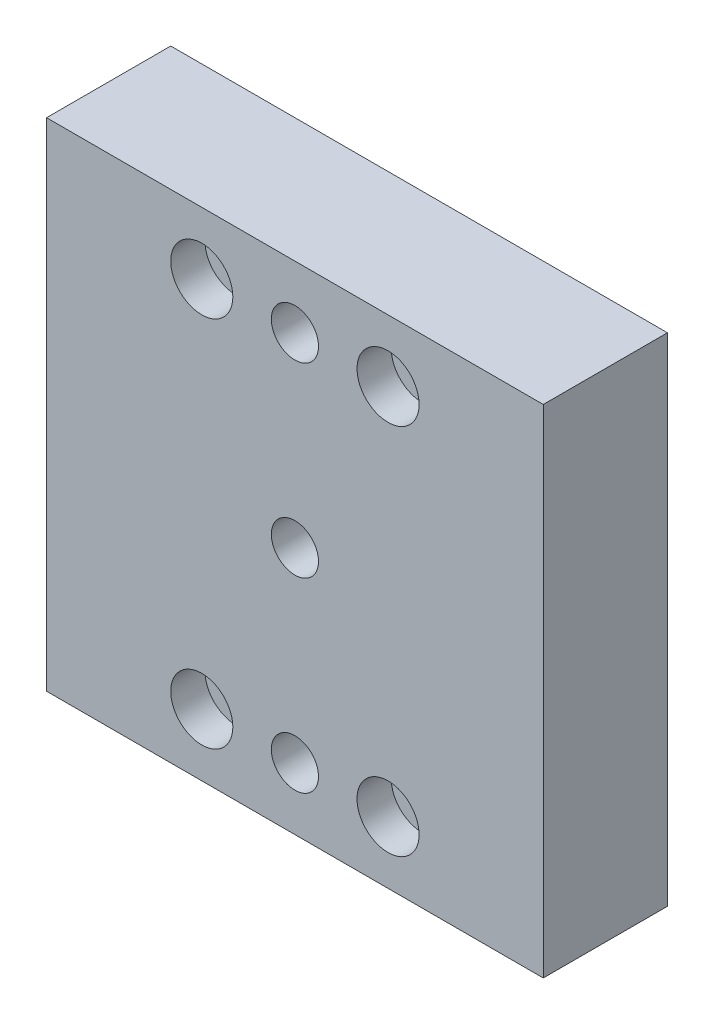
SolidWorks part; units mm, degrees
ref_plane "Front" through (0, 0, 0) normal (0, 0, 1) x (1, 0, 0)
ref_plane "Top" through (0, 0, 0) normal (0, 1, 0) x (1, 0, 0)
ref_plane "Right" through (0, 0, 0) normal (1, 0, 0) x (0, 0, -1)
sketch "Sketch1" plane through (0, 0, 0) normal (0, 0, 1) x (1, 0, 0)
  line L1 (-25.4, -25.4) -> (25.4, -25.4)
  line L2 (-25.4, -25.4) -> (-25.4, 25.4)
  line L3 (-25.4, 25.4) -> (25.4, 25.4)
  line L4 (25.4, -25.4) -> (25.4, 25.4)
  line L5 (-25.4, -25.4) -> (25.4, 25.4) construction
  line L6 (-25.4, 25.4) -> (25.4, -25.4) construction
  point P0 (0, 0)
  dimension "D1" = 50.8
  dimension "D2" = 50.8
extrude "Boss-Extrude1" add sketch "Sketch1" along normal blind 12.7
sketch "Sketch2" plane through (0, 0, 12.7) normal (0, 0, 1) x (1, 0, 0)
  line L0 (0, 25.4) -> (0, -25.4) construction
  line L1 (25.4, 25.4) -> (-25.4, 25.4) construction
  line L2 (-25.4, -25.4) -> (25.4, -25.4) construction
  point P6 (0, 19.05)
  point P7 (0, 0)
  point P9 (0, -19.05)
  dimension "D1" = 6.35
  dimension "D2" = 19.05
  dimension "D3" = 6.35
hole_wizard "#10 CB" positions "Sketch4" profile "Sketch3" counterbore size "#10" standard "ANSI Inch" end condition through all
sketch "Sketch4" plane through (0, 0, 0) normal (0, 0, 1) x (1, 0, 0)
  point P0 (0, 19.05)
  point P3 (0, 0)
  point P9 (0, -19.05)
sketch "Sketch3" plane through (0, 19.05, 0) normal (1, 0, 0) x (0, 1, 0)
  line L0 (0, 0) -> (0, 12.7)
  line L1 (0, 12.7) -> (2.413, 12.7)
  line L3 (2.413, 12.7) -> (2.413, 4.826)
  line L4 (2.413, 4.826) -> (3.175, 4.826)
  line L5 (3.175, 4.826) -> (3.175, 0)
  line L7 (3.175, 0) -> (0, 0)
  line L11 (0, -6.35) -> (0, 107.95) construction
  dimension "Thru Hole Dia." = 4.826
  dimension "Thru Hole Depth" = 12.7
  dimension "C'Bore Dia." = 6.35
  dimension "C'Bore Depth" = 4.826
hole_wizard "#6 CB" positions "Sketch6" profile "Sketch5" counterbore size "#10" standard "ANSI Inch"
sketch "Sketch6" plane through (0, 0, 12.7) normal (0, 0, 1) x (1, 0, 0)
  line L4 (0, 25.4) -> (0, -25.4) construction
  line L5 (0, 25.4) -> (0, -25.4) construction
  line L6 (25.4, 25.4) -> (-25.4, 25.4) construction
  point P0 (-9.525, 19.05)
  point P2 (-9.525, -19.05)
  point P4 (9.525, -19.05)
  point P6 (9.525, 19.05)
  dimension "D1" = 19.05
  dimension "D2" = 38.1
  dimension "D3" = 6.35
sketch "Sketch5" plane through (-9.525, 19.05, 12.7) normal (1, 0, 0) x (0, -1, 0)
  line L0 (0, 0) -> (0, 50.8)
  line L1 (0, 50.8) -> (1.7526, 50.8)
  line L2 (1.7526, 50.8) -> (1.7526, 3.5052)
  line L3 (1.7526, 3.5052) -> (3.175, 3.5052)
  line L4 (3.175, 3.5052) -> (3.175, 0)
  line L5 (3.175, 0) -> (0, 0)
  line L10 (0, 50.8) -> (-1.7526, 50.8) construction
  line L11 (0, -6.35) -> (0, 107.95) construction
  dimension "Hole Dia." = 3.5052
  dimension "Hole Depth" = 50.8
  dimension "C'Bore Dia." = 6.35
  dimension "C'Bore Depth" = 3.5052
  dimension "Drill Angle" = 180
